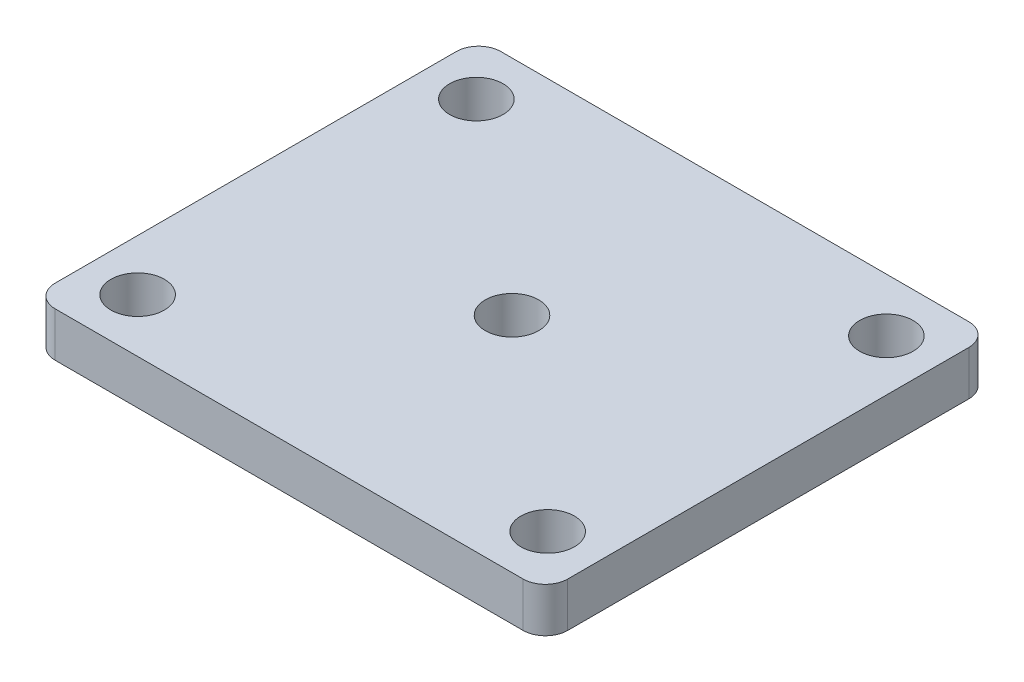
SolidWorks part; units mm, degrees
material "Stainless Steel (ferritic)"
ref_plane "Front Plane" through (0, 0, 0) normal (0, 0, 1) x (1, 0, 0)
ref_plane "Top Plane" through (0, 0, 0) normal (0, 1, 0) x (1, 0, 0)
ref_plane "Right Plane" through (0, 0, 0) normal (1, 0, 0) x (0, 0, -1)
sketch "Sketch1" plane through (0, 0, 0) normal (0, 1, 0) x (1, 0, 0)
  line L1 (57.5, -50) -> (-57.5, -50)
  line L2 (57.5, -50) -> (57.5, 50)
  line L3 (57.5, 50) -> (-57.5, 50)
  line L4 (-57.5, -50) -> (-57.5, 50)
  line L5 (57.5, -50) -> (-57.5, 50) construction
  line L6 (57.5, 50) -> (-57.5, -50) construction
  line L23 (46, -38) -> (-46, -38) construction
  line L29 (46, -38) -> (46, 38) construction
  line L35 (0, 0) -> (0, 13.2685) construction
  line L36 (0, 0) -> (9.6976, 0) construction
  line L37 (46, 38) -> (-46, 38) construction
  line L56 (-46, -38) -> (-46, 38) construction
  line L59 (46, -38) -> (-46, 38) construction
  line L62 (46, 38) -> (-46, -38) construction
  circle A0 centre (-46, 38) radius 6
  circle A1 centre (46, 38) radius 6
  circle A2 centre (46, -38) radius 6
  circle A3 centre (-46, -38) radius 6
  circle A4 centre (0, 0) radius 6
  point P0 (0, 0)
  dimension "D5" = 12
  dimension "D6" = 12
  dimension "D1" = 115
  dimension "D2" = 100
  dimension "D3" = 92
  dimension "D4" = 76
extrude "Boss-Extrude2" add sketch "Sketch1" along normal blind 10
fillet "Fillet1" radius 5 4 edges at (-57.5, 5, -50) (57.5, 5, -50) (57.5, 5, 50) (-57.5, 5, 50)
